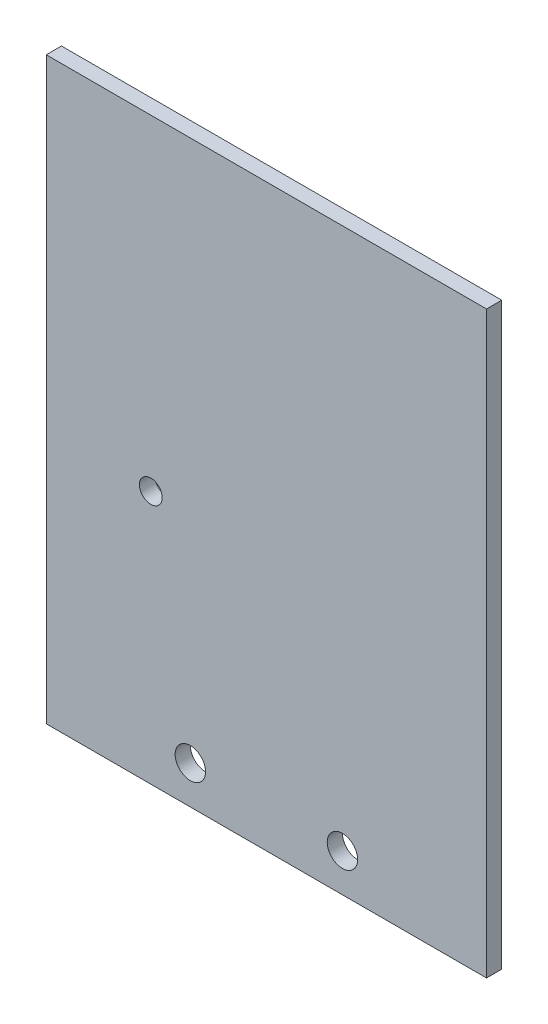
SolidWorks part; units mm, degrees
ref_plane "Front Plane" through (0, 0, 0) normal (0, 0, 1) x (1, 0, 0)
ref_plane "Top Plane" through (0, 0, 0) normal (0, 1, 0) x (1, 0, 0)
ref_plane "Right Plane" through (0, 0, 0) normal (1, 0, 0) x (0, 0, -1)
sketch "Sketch1" plane through (0, 0, 0) normal (0, 0, 1) x (1, 0, 0)
  line L1 (-35.5404, 29.2034) -> (22.3596, 29.2034)
  line L2 (-35.5404, 29.2034) -> (-35.5404, -46.9966)
  line L3 (-35.5404, -46.9966) -> (22.3596, -46.9966)
  line L4 (22.3596, 29.2034) -> (22.3596, -46.9966)
  dimension "D1" = 57.9
  dimension "D2" = 76.2
extrude "Boss-Extrude1" add sketch "Sketch1" along normal blind 2
sketch "Sketch2" plane through (0, 0, 0) normal (0, 0, -1) x (-1, 0, 0)
  line L0 (6.5904, 29.2034) -> (6.5904, 20.2034)
  line L1 (-22.3596, 29.2034) -> (35.5404, 29.2034) construction
  line L2 (26.9623, 24.7034) -> (-15.5564, 24.7034) construction
  line L3 (-6.4096, 24.7034) -> (19.5904, 24.7034)
  line L4 (19.5904, 24.7034) -> (19.5904, 14.2034)
  line L5 (19.5904, 14.2034) -> (-6.4096, 14.2034)
  line L6 (-3.3596, 4.2034) -> (8.6404, 4.2034)
  line L7 (-22.3596, 29.2034) -> (2.6404, 29.2034)
  line L8 (-22.3596, 29.2034) -> (-22.3596, 4.2034)
  line L9 (-22.3596, 4.2034) -> (2.6404, 4.2034)
  line L10 (2.6404, 29.2034) -> (2.6404, 4.2034)
  line L11 (2.6404, 4.2034) -> (2.6404, 9.2034)
  line L12 (12.201, -46.9966) -> (12.201, -41.9966)
  line L13 (8.6404, 9.2034) -> (-3.3596, 9.2034)
  line L14 (8.6404, 9.2034) -> (8.6404, -0.7966)
  line L15 (8.6404, -0.7966) -> (-3.3596, -0.7966)
  line L16 (-3.3596, 9.2034) -> (-3.3596, -0.7966)
  line L17 (35.5404, -46.9966) -> (-22.3596, -46.9966) construction
  line L18 (35.5404, -41.9966) -> (-22.3596, -41.9966) construction
  line L19 (35.5404, 29.2034) -> (35.5404, -46.9966) construction
  line L20 (-22.3596, -46.9966) -> (-22.3596, 29.2034) construction
  line L21 (35.5404, -41.9966) -> (-22.3596, -41.9966)
  line L22 (-3.4096, -41.9966) -> (16.5904, -41.9966)
  line L24 (35.5404, 29.2034) -> (21.7904, 29.2034)
  line L25 (35.5404, 29.2034) -> (35.5404, -13.6266)
  line L26 (35.5404, -13.6266) -> (21.7904, -13.6266)
  line L27 (21.7904, 29.2034) -> (21.7904, -13.6266)
  circle A0 centre (19.5904, 14.2034) radius 2
  circle A1 centre (-6.4096, 14.2034) radius 2
  circle A2 centre (16.5904, -41.9966) radius 2
  circle A3 centre (-3.4096, -41.9966) radius 2
  circle A4 centre (21.7904, -13.6266) radius 1.5
  point P9 (6.5904, 24.7034)
  point P21 (2.6404, 4.2034)
  point P39 (6.5904, -41.9966)
  dimension "D3" = 4
  dimension "D4" = 4
  dimension "D11" = 4
  dimension "D12" = 4
  dimension "D15" = 3
  dimension "D1" = 9
  dimension "D2" = 10.5
  dimension "D5" = 25
  dimension "D6" = 6
  dimension "D7" = 5
  dimension "D8" = 10
  dimension "D9" = 12
  dimension "D10" = 5
  dimension "D13" = 42.83
  dimension "D14" = 13.75
extrude "Cut-Extrude1" cut sketch "Sketch2" against normal up to surface (2 mm away)
sketch "Sketch4" plane through (0, 0, 0) normal (0, 0, -1) x (-1, 0, 0)
  line L0 (-3.3596, 9.2034) -> (-3.3596, 18.3231)
  line L1 (6.5904, 29.2034) -> (6.5904, 14.2034)
  line L2 (-22.3596, 29.2034) -> (35.5404, 29.2034) construction
  line L3 (19.5904, 16.1606) -> (6.5904, 16.1606)
  line L5 (-13.6502, 24.4874) -> (30.1504, 24.4874)
  line L6 (-13.6502, 24.4874) -> (-13.6502, 9.2034)
  line L7 (-13.6502, 9.2034) -> (30.1504, 9.2034)
  line L8 (30.1504, 24.4874) -> (30.1504, 9.2034)
  circle A0 centre (-6.4096, 14.2034) radius 2
  circle A1 centre (19.5904, 14.2034) radius 1.9572
extrude "Boss-Extrude5" add sketch "Sketch4" against normal up to surface (2 mm away)
sketch "Sketch8" plane through (0, 0, 0) normal (0, 0, -1) x (-1, 0, 0)
  line L1 (-22.3596, 29.2034) -> (35.5404, 29.2034)
  line L2 (-22.3596, 29.2034) -> (-22.3596, -46.9966)
  line L3 (-22.3596, -46.9966) -> (35.5404, -46.9966)
  line L4 (35.5404, 29.2034) -> (35.5404, -46.9966)
  line L8 (35.5404, -46.9966) -> (35.5404, 29.2034)
  line L9 (-22.3596, -46.9966) -> (35.5404, -46.9966)
  line L10 (-22.3596, 29.2034) -> (-22.3596, -46.9966)
  line L11 (35.5404, 29.2034) -> (-22.3596, 29.2034)
  line L12 (35.5404, -46.9966) -> (35.5404, 29.2034)
  line L13 (-22.3596, -46.9966) -> (35.5404, -46.9966)
  line L14 (-22.3596, 29.2034) -> (-22.3596, -46.9966)
  line L15 (35.5404, 29.2034) -> (-22.3596, 29.2034)
  line M13 (-3.3596, 9.2034) -> (8.6404, 9.2034)
  line M14 (8.6404, 9.2034) -> (8.6404, -0.7966)
  line M15 (8.6404, -0.7966) -> (-3.3596, -0.7966)
  line M16 (-3.3596, -0.7966) -> (-3.3596, 9.2034)
  line M17 (35.5404, -46.9966) -> (35.5404, 29.2034)
  line M18 (35.5404, 29.2034) -> (-22.3596, 29.2034)
  line M19 (-22.3596, 29.2034) -> (-22.3596, -46.9966)
  line M20 (-22.3596, -46.9966) -> (35.5404, -46.9966)
  circle M21 centre (16.5904, -41.9966) radius 2
  circle M22 centre (-3.4096, -41.9966) radius 2
  circle M23 centre (21.7904, -13.6266) radius 1.5
  circle M24 centre (19.5904, 14.2034) radius 2
  dimension "D1" = 0
extrude "Boss-Extrude6" add sketch "Sketch8" along normal blind 10 contours M20 M17 M18 M19 M21 M23 M24 M22 M16 M13 M14 M15 | M24
sketch "Sketch9" plane through (0, 0, -10) normal (0, 0, -1) x (-1, 0, 0)
  line L0 (6.5318, 9.2034) -> (6.5318, 18.2034)
  line L1 (-3.3596, 9.2034) -> (8.6404, 9.2034) construction
  line L2 (6.5904, 29.2034) -> (6.5318, 18.2034)
  line L3 (35.5404, 29.2034) -> (-22.3596, 29.2034) construction
  line L4 (-6.4682, 18.2034) -> (19.5318, 18.2034)
  circle A0 centre (-6.4682, 18.2034) radius 2
  circle A1 centre (19.5318, 18.2034) radius 2
  point P10 (6.5318, 18.2034)
  dimension "D3" = 4
  dimension "D4" = 4
  dimension "D1" = 9
  dimension "D2" = 13
extrude "Cut-Extrude6" cut sketch "Sketch9" against normal blind 10
sketch "Sketch10" plane through (0, 0, 2) normal (0, 0, 1) x (1, 0, 0)
  line L1 (-35.5404, 29.2034) -> (22.3596, 29.2034)
  line L2 (-35.5404, 29.2034) -> (-35.5404, -46.9966)
  line L3 (-35.5404, -46.9966) -> (22.3596, -46.9966)
  line L4 (22.3596, 29.2034) -> (22.3596, -46.9966)
extrude "Cut-Extrude7" cut sketch "Sketch10" against normal blind 10
sketch "Sketch11" plane through (0, 0, -8) normal (0, 0, 1) x (1, 0, 0)
  line L1 (-29.6655, 22.8711) -> (15.4281, 22.8711)
  line L2 (-29.6655, 22.8711) -> (-29.6655, -4.6053)
  line L3 (-29.6655, -4.6053) -> (15.4281, -4.6053)
  line L4 (15.4281, 22.8711) -> (15.4281, -4.6053)
extrude "Boss-Extrude7" add sketch "Sketch11" against normal up to surface (2 mm away) up to face at (4.4682, 18.2034, -10)
